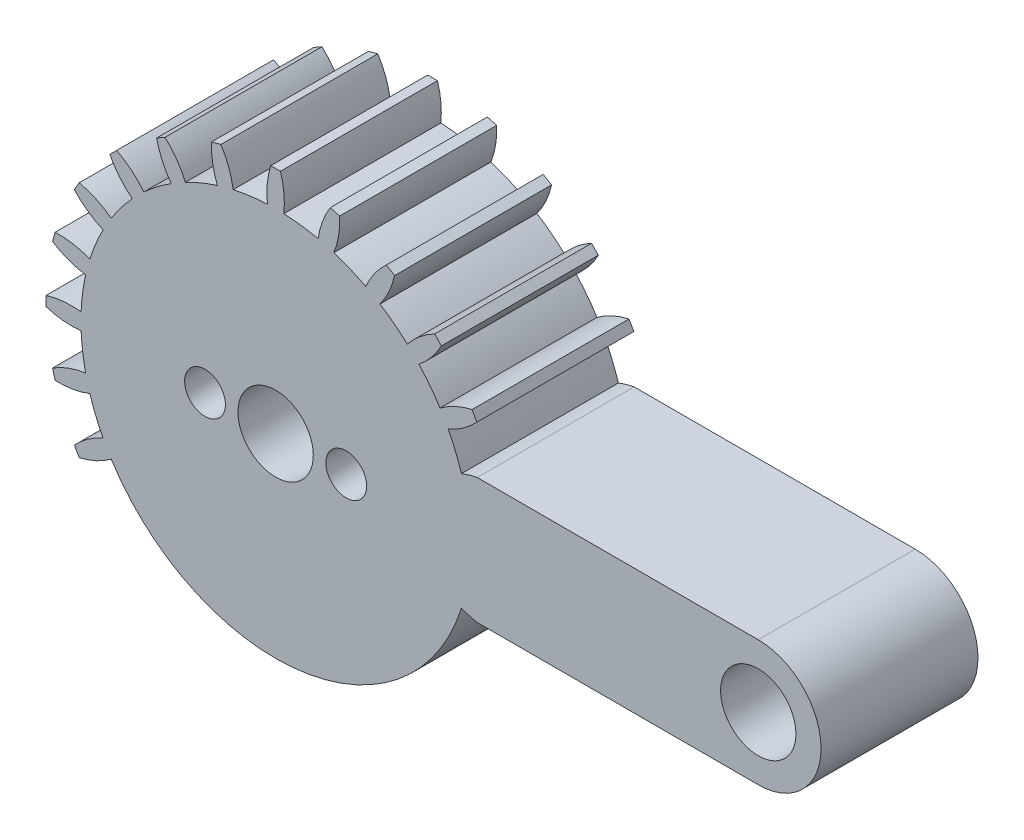
SolidWorks part; units mm, degrees
ref_plane "Front Plane" through (0, 0, 0) normal (0, 0, 1) x (1, 0, 0)
ref_plane "Top Plane" through (0, 0, 0) normal (0, 1, 0) x (1, 0, 0)
ref_plane "Right Plane" through (0, 0, 0) normal (1, 0, 0) x (0, 0, -1)
sketch "Sketch1" plane through (0, 0, 0) normal (0, 0, 1) x (1, 0, 0)
  line L0 (0, -14.63) -> (0, 14.63) construction
  line L1 (-0.31, 14.63) -> (0.31, 14.63)
  line L2 (3.4871, 14.2117) -> (4.086, 14.0513)
  line L3 (7.0465, 12.825) -> (7.5835, 12.515)
  line L4 (10.1258, 10.5642) -> (10.5642, 10.1258)
  line L5 (12.515, 7.5835) -> (12.825, 7.0465)
  line L6 (14.0513, 4.086) -> (14.2117, 3.4871)
  line L7 (14.63, 0.31) -> (14.63, -0.31)
  line L8 (14.2117, -3.4871) -> (14.0513, -4.086)
  line L9 (12.825, -7.0465) -> (12.515, -7.5835)
  line L10 (10.5642, -10.1258) -> (10.1258, -10.5642)
  line L11 (7.5835, -12.515) -> (7.0465, -12.825)
  line L12 (4.086, -14.0513) -> (3.4871, -14.2117)
  line L13 (0.31, -14.63) -> (-0.31, -14.63)
  line L14 (-3.4871, -14.2117) -> (-4.086, -14.0513)
  line L15 (-7.0465, -12.825) -> (-7.5835, -12.515)
  line L16 (-10.1258, -10.5642) -> (-10.5642, -10.1258)
  line L17 (-12.515, -7.5835) -> (-12.825, -7.0465)
  line L18 (-14.0513, -4.086) -> (-14.2117, -3.4871)
  line L19 (-14.63, -0.31) -> (-14.63, 0.31)
  line L20 (-14.2117, 3.4871) -> (-14.0513, 4.086)
  line L21 (-12.825, 7.0465) -> (-12.515, 7.5835)
  line L22 (-10.5642, 10.1258) -> (-10.1258, 10.5642)
  line L23 (-7.5835, 12.515) -> (-7.0465, 12.825)
  line L24 (-4.086, 14.0513) -> (-3.4871, 14.2117)
  line L25 (30.75, -4) -> (30.75, 4) construction
  line L26 (30.75, 4) -> (11.7424, 4)
  line L27 (30.75, 0) -> (0, 0) construction
  line L28 (30.75, -4) -> (11.7424, -4)
  circle A0 centre (0, 0) radius 12.405
  circle A1 centre (0, 0) radius 2
  circle A2 centre (30.75, 0) radius 2.4
  arc A3 (-0.52, 12.3941) -> (-0.31, 14.63) centre (4.8438, 13.0181) cw
  arc A4 (-0.52, 16.8659) -> (-0.31, 14.63) centre (4.8438, 16.2419) ccw
  arc A5 (0.52, 12.3941) -> (0.31, 14.63) centre (-4.8438, 13.0181) ccw
  arc A6 (2.7055, 12.1064) -> (3.4871, 14.2117) centre (8.0481, 11.3209) cw
  arc A7 (3.7101, 11.8372) -> (4.086, 14.0513) centre (-1.3094, 13.8282) ccw
  arc A8 (5.7467, 10.9936) -> (7.0465, 12.825) centre (10.7039, 8.8521) cw
  arc A9 (6.6474, 10.4736) -> (7.5835, 12.515) centre (2.3142, 13.6959) ccw
  arc A10 (8.3963, 9.1316) -> (10.1258, 10.5642) centre (12.6303, 5.7801) cw
  arc A11 (9.1316, 8.3963) -> (10.5642, 10.1258) centre (5.7801, 12.6303) ccw
  arc A12 (10.4736, 6.6474) -> (12.515, 7.5835) centre (13.6959, 2.3142) cw
  arc A13 (10.9936, 5.7467) -> (12.825, 7.0465) centre (8.8521, 10.7039) ccw
  arc A14 (11.8372, 3.7101) -> (14.0513, 4.086) centre (13.8282, -1.3094) cw
  arc A15 (12.1064, 2.7055) -> (14.2117, 3.4871) centre (11.3209, 8.0481) ccw
  arc A16 (12.3941, 0.52) -> (14.63, 0.31) centre (13.0181, -4.8438) cw
  arc A17 (12.3941, -0.52) -> (14.63, -0.31) centre (13.0181, 4.8438) ccw
  arc A18 (12.1064, -2.7055) -> (14.2117, -3.4871) centre (11.3209, -8.0481) cw
  arc A19 (11.8372, -3.7101) -> (14.0513, -4.086) centre (13.8282, 1.3094) ccw
  arc A20 (10.9936, -5.7467) -> (12.825, -7.0465) centre (8.8521, -10.7039) cw
  arc A21 (10.4736, -6.6474) -> (12.515, -7.5835) centre (13.6959, -2.3142) ccw
  arc A22 (9.1316, -8.3963) -> (10.5642, -10.1258) centre (5.7801, -12.6303) cw
  arc A23 (8.3963, -9.1316) -> (10.1258, -10.5642) centre (12.6303, -5.7801) ccw
  arc A24 (6.6474, -10.4736) -> (7.5835, -12.515) centre (2.3142, -13.6959) cw
  arc A25 (5.7467, -10.9936) -> (7.0465, -12.825) centre (10.7039, -8.8521) ccw
  arc A26 (3.7101, -11.8372) -> (4.086, -14.0513) centre (-1.3094, -13.8282) cw
  arc A27 (2.7055, -12.1064) -> (3.4871, -14.2117) centre (8.0481, -11.3209) ccw
  arc A28 (0.52, -12.3941) -> (0.31, -14.63) centre (-4.8438, -13.0181) cw
  arc A29 (-0.52, -12.3941) -> (-0.31, -14.63) centre (4.8438, -13.0181) ccw
  arc A30 (-2.7055, -12.1064) -> (-3.4871, -14.2117) centre (-8.0481, -11.3209) cw
  arc A31 (-3.7101, -11.8372) -> (-4.086, -14.0513) centre (1.3094, -13.8282) ccw
  arc A32 (-5.7467, -10.9936) -> (-7.0465, -12.825) centre (-10.7039, -8.8521) cw
  arc A33 (-6.6474, -10.4736) -> (-7.5835, -12.515) centre (-2.3142, -13.6959) ccw
  arc A34 (-8.3963, -9.1316) -> (-10.1258, -10.5642) centre (-12.6303, -5.7801) cw
  arc A35 (-9.1316, -8.3963) -> (-10.5642, -10.1258) centre (-5.7801, -12.6303) ccw
  arc A36 (-10.4736, -6.6474) -> (-12.515, -7.5835) centre (-13.6959, -2.3142) cw
  arc A37 (-10.9936, -5.7467) -> (-12.825, -7.0465) centre (-8.8521, -10.7039) ccw
  arc A38 (-11.8372, -3.7101) -> (-14.0513, -4.086) centre (-13.8282, 1.3094) cw
  arc A39 (-12.1064, -2.7055) -> (-14.2117, -3.4871) centre (-11.3209, -8.0481) ccw
  arc A40 (-12.3941, -0.52) -> (-14.63, -0.31) centre (-13.0181, 4.8438) cw
  arc A41 (-12.3941, 0.52) -> (-14.63, 0.31) centre (-13.0181, -4.8438) ccw
  arc A42 (-12.1064, 2.7055) -> (-14.2117, 3.4871) centre (-11.3209, 8.0481) cw
  arc A43 (-11.8372, 3.7101) -> (-14.0513, 4.086) centre (-13.8282, -1.3094) ccw
  arc A44 (-10.9936, 5.7467) -> (-12.825, 7.0465) centre (-8.8521, 10.7039) cw
  arc A45 (-10.4736, 6.6474) -> (-12.515, 7.5835) centre (-13.6959, 2.3142) ccw
  arc A46 (-9.1316, 8.3963) -> (-10.5642, 10.1258) centre (-5.7801, 12.6303) cw
  arc A47 (-8.3963, 9.1316) -> (-10.1258, 10.5642) centre (-12.6303, 5.7801) ccw
  arc A48 (-6.6474, 10.4736) -> (-7.5835, 12.515) centre (-2.3142, 13.6959) cw
  arc A49 (-5.7467, 10.9936) -> (-7.0465, 12.825) centre (-10.7039, 8.8521) ccw
  arc A50 (-3.7101, 11.8372) -> (-4.086, 14.0513) centre (1.3094, 13.8282) cw
  arc A51 (-2.7055, 12.1064) -> (-3.4871, 14.2117) centre (-8.0481, 11.3209) ccw
  arc A52 (30.75, -4) -> (30.75, 4) centre (30.75, 0) ccw
  point P12 (0, 0)
  point P158 (0, 0)
  point P160 (30.75, 0)
  dimension "D1" = 24.81
  dimension "D2" = 4
  dimension "D3" = 4.8
  dimension "D6" = 5.4
  dimension "D10" = 8
  dimension "D4" = 30.75
  dimension "D5" = 29.26
  dimension "D7" = 0.31
  dimension "D8" = 1.04
  dimension "D9" = 24
extrude "Boss-Extrude1" add sketch "Sketch1" along normal blind 10 contours L28 A52 L26 L6 A15 A0 A16 L7 A17 A18 L8 A2 | A0 | A0 A13 L5 A12 | A0 A11 L4 A10 | A0 A9 L3 A8 | A0 A7 L2 A6 | A0 A5 L1 A3 | A0 A51 L24 A50 | A0 A49 L23 A48 | A0 A47 L22 A46 | A0 A45 L21 A44 | A0 A43 L20 A42 | A0 A41 L19 A40 | A0 A39 L18 A38 | A0 A15 L6 L26 A14 | A0 A17 L7 A16 | A0 A19 L28 L8 A18 | A0 A37 L17 A36
sketch "Sketch2" plane through (0, 0, 10) normal (0, 0, 1) x (1, 0, 0)
  line L0 (-4.5, 0) -> (4.5, 0) construction
  circle A0 centre (0, 0) radius 2.4
  circle A1 centre (4.5, 0) radius 1.3
  circle A2 centre (-4.5, 0) radius 1.3
  point P5 (0, 0)
  dimension "D2" = 2.6
  dimension "D3" = 2.6
  dimension "D4" = 4.8
  dimension "D1" = 9
extrude "Cut-Extrude1" cut sketch "Sketch2" against normal through all
